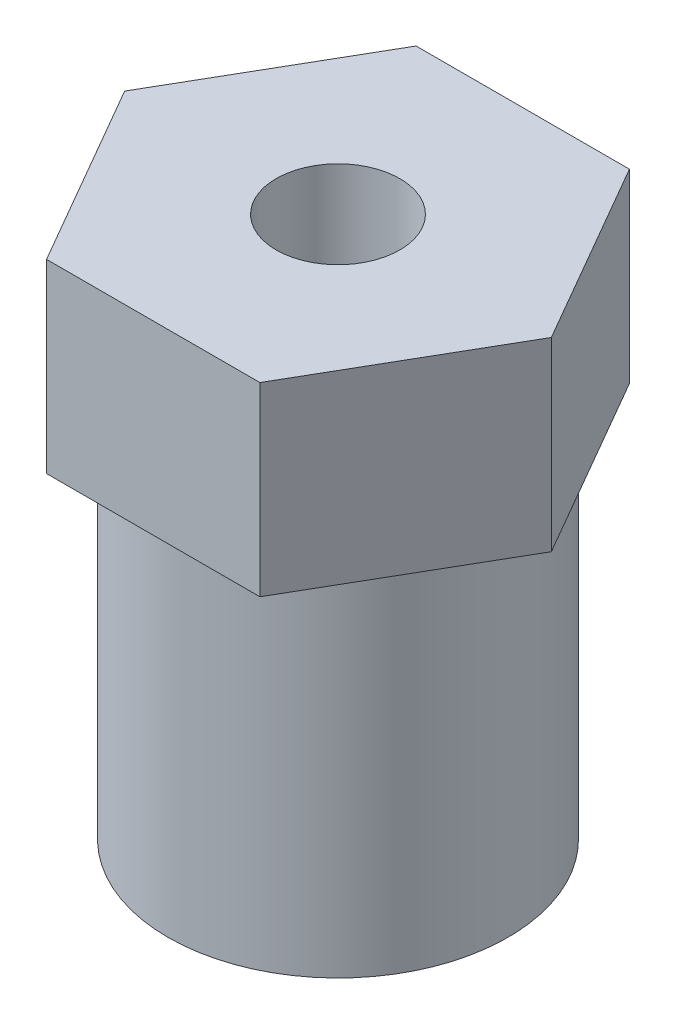
SolidWorks part; units mm, degrees
material "AISI 304"
ref_plane "前视基准面" through (0, 0, 0) normal (0, 0, 1) x (1, 0, 0)
ref_plane "上视基准面" through (0, 0, 0) normal (0, 1, 0) x (1, 0, 0)
ref_plane "右视基准面" through (0, 0, 0) normal (1, 0, 0) x (0, 0, -1)
other "Configuration Table"
sketch "草图1" plane through (0, 0, 0) normal (0, 1, 0) x (1, 0, 0)
  line L1 (6.8993, 0) -> (3.4497, 5.975)
  line L2 (3.4497, 5.975) -> (-3.4497, 5.975)
  line L3 (-3.4497, 5.975) -> (-6.8993, 0)
  line L4 (-6.8993, 0) -> (-3.4497, -5.975)
  line L5 (-3.4497, -5.975) -> (3.4497, -5.975)
  line L6 (3.4497, -5.975) -> (6.8993, 0)
  circle A0 centre (0, 0) radius 5.975 construction
  circle A1 centre (0, 0) radius 2
  dimension "D2" = 4
  dimension "D1" = 11.95
extrude "凸台-拉伸1" add sketch "草图1" along normal blind 6
sketch "草图2" plane through (0, 0, 0) normal (0, -1, 0) x (1, 0, 0)
  circle A0 centre (0, 0) radius 5.5
  circle A1 centre (0, 0) radius 2.5
  dimension "D1" = 5
  dimension "D2" = 11
extrude "凸台-拉伸2" add sketch "草图2" along normal blind 11.5
